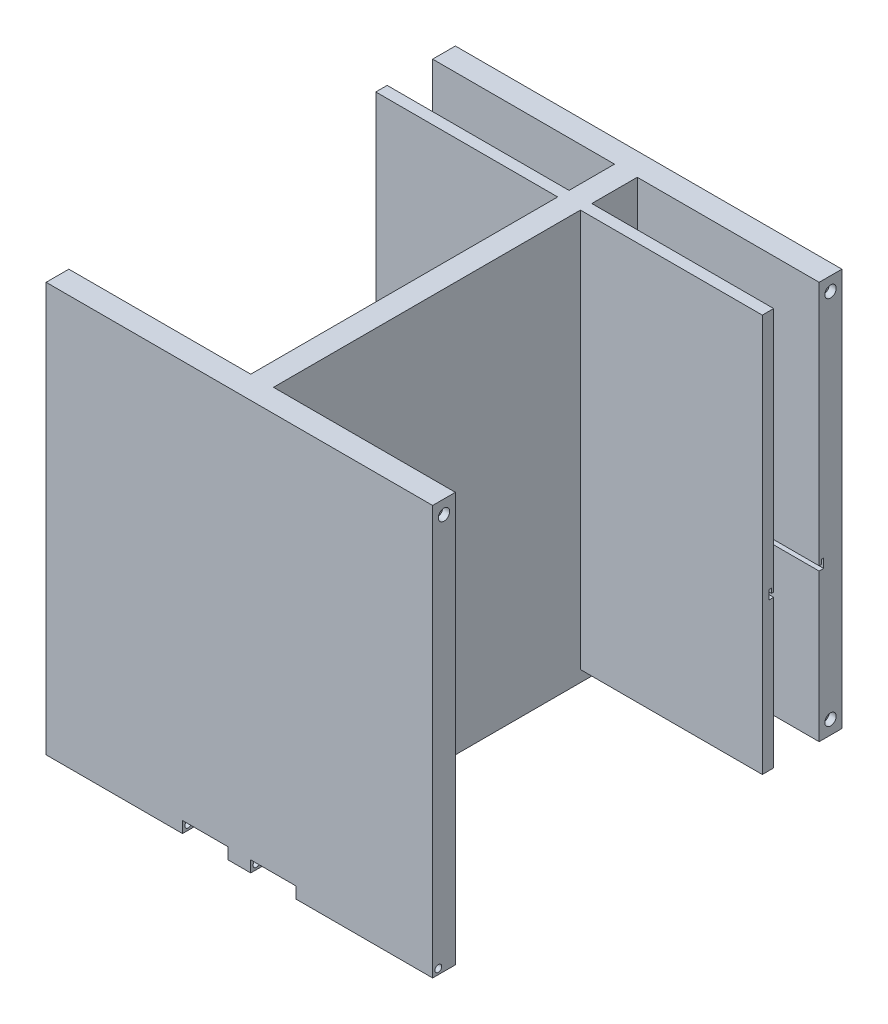
SolidWorks part; units mm, degrees
ref_plane "Front Plane" through (0, 0, 0) normal (0, 0, 1) x (1, 0, 0)
ref_plane "Top Plane" through (0, 0, 0) normal (0, 1, 0) x (1, 0, 0)
ref_plane "Right Plane" through (0, 0, 0) normal (1, 0, 0) x (0, 0, -1)
sketch "Sketch1" plane through (0, 0, 0) normal (0, 1, 0) x (1, 0, 0)
  line L1 (-45, -45) -> (45, -45)
  line L2 (-45, -45) -> (-45, 45)
  line L3 (-45, 45) -> (45, 45)
  line L4 (45, -45) -> (45, 45)
  line L5 (-45, -45) -> (45, 45) construction
  line L6 (-45, 45) -> (45, -45) construction
  point P0 (0, 0)
  dimension "D1" = 90
  dimension "D2" = 90
extrude "Boss-Extrude1" add sketch "Sketch1" along normal blind 90
sketch "Sketch4" plane through (0, 90, 0) normal (0, 1, 0) x (1, 0, 0)
  line L0 (0, 45) -> (0, -45) construction
  line L1 (45, 45) -> (-45, 45) construction
  line L2 (-45, -45) -> (45, -45) construction
  line L3 (-45, 45) -> (-45, -45) construction
  line L4 (-2.5, -40) -> (2.5, -40)
  line L5 (-2.5, -40) -> (-2.5, 40)
  line L6 (-2.5, 40) -> (2.5, 40)
  line L7 (2.5, -40) -> (2.5, 40)
  line L8 (-2.5, -40) -> (2.5, 40) construction
  line L9 (-2.5, 40) -> (2.5, -40) construction
  line L10 (-2.5, 40) -> (-42.5, 40)
  line L11 (-2.5, 40) -> (-2.5, -40)
  line L12 (-2.5, -40) -> (-42.5, -40)
  line L13 (-42.5, 40) -> (-42.5, -40)
  line L14 (2.5, -40) -> (42.5, -40)
  line L15 (42.5, 40) -> (42.5, -40)
  line L16 (2.5, 40) -> (42.5, 40)
  line L17 (2.5, 40) -> (2.5, -40)
  point P6 (0, 0)
  dimension "D1" = 80
  dimension "D2" = 5
  dimension "D3" = 2.5
extrude "Cut-Extrude3" cut sketch "Sketch4" against normal blind 90 contours L12 L13 L10 L5 | L15 L14 L7 L16
sketch "Sketch6" plane through (0, 0, 45) normal (0, 0, 1) x (1, 0, 0)
  line L0 (0, 90) -> (0, 0) construction
  line L1 (-45, 90) -> (45, 90) construction
  line L2 (2.5, 2.5) -> (12.5, 2.5)
  line L3 (-2.5, 0) -> (2.5, 0)
  line L4 (-2.5, 0) -> (-2.5, 90)
  line L5 (-2.5, 90) -> (2.5, 90)
  line L6 (2.5, 0) -> (2.5, 90)
  line L7 (-2.5, 0) -> (2.5, 90) construction
  line L8 (-2.5, 90) -> (2.5, 0) construction
  line L9 (-2.5, 0) -> (-12.5, 0)
  line L10 (-2.5, 0) -> (-2.5, 2.5)
  line L11 (-2.5, 2.5) -> (-12.5, 2.5)
  line L12 (-12.5, 0) -> (-12.5, 2.5)
  line L13 (12.5, 0) -> (12.5, 2.5)
  line L14 (2.5, 0) -> (12.5, 0)
  line L15 (2.5, 0) -> (2.5, 2.5)
  point P5 (0, 45)
  dimension "D1" = 5
  dimension "D2" = 2.5
  dimension "D3" = 10
extrude "Cut-Extrude5" cut sketch "Sketch6" against normal blind 10 contours L15 L2 L13 L14 | L10 L11 L12 L9
sketch "Sketch7" plane through (0, 90, 0) normal (0, 1, 0) x (1, 0, 0)
  line L0 (42.5, 40) -> (42.5, 45)
  line L1 (45, 45) -> (-45, 45) construction
  line L2 (42.5, -40) -> (42.5, -45)
  line L3 (-45, -45) -> (45, -45) construction
  line L4 (42.5, 45) -> (45, 45)
  line L5 (45, 45) -> (45, -45)
  line L6 (45, -45) -> (42.5, -45)
  line L7 (42.5, 40) -> (42.5, -40)
extrude "Cut-Extrude6" cut sketch "Sketch7" against normal blind 90 contours L4 L5 L6 L2 L7 L0
sketch "Sketch8" plane through (0, 90, 0) normal (0, 1, 0) x (1, 0, 0)
  line L0 (-42.5, 40) -> (-42.5, 45)
  line L1 (42.5, 45) -> (-45, 45) construction
  line L2 (-42.5, 45) -> (-45, 45)
  line L3 (-45, 45) -> (-45, -45)
  line L4 (-45, -45) -> (-42.5, -45)
  line L5 (-45, -45) -> (42.5, -45) construction
  line L6 (-42.5, -45) -> (-42.5, -42.5)
  line L7 (-42.5, 40) -> (-42.5, -40) construction
  line L8 (-42.5, -42.5) -> (-42.5, 40)
extrude "Cut-Extrude7" cut sketch "Sketch8" against normal blind 90
sketch "Sketch10" plane through (-2.5, 0, 0) normal (-1, 0, 0) x (0, 0, 1)
  line L0 (40, 90) -> (-40, 90) construction
  line L1 (-27.5, 90) -> (-30, 90)
  line L2 (-27.5, 90) -> (-27.5, 0)
  line L3 (-27.5, 0) -> (-30, 0)
  line L4 (-30, 90) -> (-30, 0)
  line L5 (45, 0) -> (-40, 0) construction
  line L6 (-40, 0) -> (-40, 90) construction
  dimension "D1" = 10
  dimension "D2" = 2.5
extrude "Boss-Extrude2" add sketch "Sketch10" along normal blind 40 contours L1 L4 L3 L2
sketch "Sketch11" plane through (2.5, 0, 0) normal (1, 0, 0) x (0, 0, -1)
  line L0 (-45, 0) -> (40, 0) construction
  line L1 (27.5, 90) -> (30, 90)
  line L2 (27.5, 90) -> (27.5, 0)
  line L3 (27.5, 0) -> (30, 0)
  line L4 (30, 90) -> (30, 0)
  line L5 (40, 0) -> (40, 90) construction
  dimension "D1" = 10
  dimension "D2" = 2.5
extrude "Boss-Extrude3" add sketch "Sketch11" along normal blind 40
sketch "Sketch13" plane through (42.5, 0, 0) normal (1, 0, 0) x (0, 0, -1)
  line L0 (35, 90) -> (35, 0) construction
  line L1 (30, 90) -> (40, 90) construction
  line L2 (30, 0) -> (40, 0) construction
  line L13 (40, 36) -> (40.5, 36)
  line L14 (40, 0) -> (40, 90) construction
  line L15 (40.5, 36) -> (40.5, 37)
  line L16 (40.5, 37) -> (41, 37)
  line L17 (41, 37) -> (41, 35)
  line L18 (41, 35) -> (40, 35)
  line L19 (40, 35) -> (40, 36)
  line L20 (40, 0) -> (45, 0) construction
  line L21 (29, 35) -> (30, 35)
  line L22 (29, 37) -> (29, 35)
  line L23 (29.5, 37) -> (29, 37)
  line L24 (29.5, 36) -> (29.5, 37)
  line L25 (30, 36) -> (29.5, 36)
  line L26 (30, 35) -> (30, 36)
  dimension "D1" = 2
  dimension "D2" = 1
  dimension "D3" = 0.5
  dimension "D4" = 35
  dimension "D5" = 1
extrude "Cut-Extrude10" cut sketch "Sketch13" against normal blind 37.5 contours L13 L15 L16 L17 L18 L19 | L22 L21 L26 L25 L24 L23
ref_plane "Plane1" through (0, 0, 0) normal (-1, 0, 0) x (0, 0, 1)
mirror "Mirror1" about plane through (0, 0, 0) normal (-1, 0, 0) of "Cut-Extrude10"
sketch "Sketch16" plane through (-12.5, 0, 0) normal (1, 0, 0) x (0, 0, -1)
  line L0 (-40, 0) -> (-45, 0) construction
  line L1 (-45, 0) -> (-45, 2.5) construction
  circle A0 centre (-43.75, 1.2) radius 0.75
  dimension "D1" = 1.5
  dimension "D2" = 1.2
  dimension "D3" = 1.25
extrude "Cut-Extrude12" cut sketch "Sketch16" against normal blind 1.5
sketch "Sketch17" plane through (-2.5, 0, 0) normal (-1, 0, 0) x (0, 0, 1)
  line L0 (45, 0) -> (45, 2.5) construction
  line L1 (45, 0) -> (-27.5, 0) construction
  circle A0 centre (43.75, 1.2) radius 0.75
  dimension "D1" = 1.5
  dimension "D2" = 1.25
  dimension "D3" = 1.2
extrude "Cut-Extrude13" cut sketch "Sketch17" along normal through all both and the other way through all
sketch "Sketch21" plane through (42.5, 0, 0) normal (1, 0, 0) x (0, 0, -1)
  line L0 (-40, 0) -> (-40, 2.5)
  line L1 (-45, 0) -> (27.5, 0) construction
  line L2 (-40, 2.5) -> (-40, 90) construction
  line L3 (-40, 2.5) -> (45, 2.5)
  line L4 (45, 0) -> (45, 90) construction
  line L5 (45, 2.5) -> (45, 0)
  line L6 (45, 0) -> (-40, 0)
  line L7 (-45, 0) -> (-40, 0) construction
  point P6 (-40, 0)
  dimension "D1" = 2.5
extrude "Cut-Extrude14" cut sketch "Sketch21" against normal blind 40
sketch "Sketch22" plane through (-42.5, 0, 0) normal (-1, 0, 0) x (0, 0, 1)
  line L6 (40, 0) -> (40, 2.5)
  line L7 (40, 2.5) -> (40, 90) construction
  line L8 (40, 2.5) -> (-45, 2.5)
  line L9 (-45, 0) -> (-45, 90) construction
  line L10 (-45, 2.5) -> (-45, 0)
  line L11 (-45, 0) -> (40, 0)
  dimension "D1" = 2.5
extrude "Cut-Extrude15" cut sketch "Sketch22" against normal blind 40
sketch "Sketch23" plane through (42.5, 0, 0) normal (1, 0, 0) x (0, 0, -1)
  line L0 (42.5, 90) -> (42.5, 2.5) construction
  line L1 (45, 90) -> (40, 90) construction
  line L2 (45, 2.5) -> (40, 2.5) construction
  line L3 (45, 2.5) -> (45, 90) construction
  line L4 (45, 46.25) -> (40, 46.25) construction
  line L5 (40, 2.5) -> (40, 90) construction
  circle A0 centre (42.5, 87) radius 1.25
  circle A1 centre (42.5, 5.5) radius 1.25
  dimension "D3" = 2.5
  dimension "D1" = 2.5
  dimension "D2" = 3
extrude "Cut-Extrude16" cut sketch "Sketch23" against normal blind 1.5
sketch "Sketch24" plane through (42.5, 0, 0) normal (1, 0, 0) x (0, 0, -1)
  line L0 (-42.8174, 90) -> (-42.5, 90) construction
  line L1 (-40, 90) -> (-45, 90) construction
  line L2 (-42.5, 90) -> (-42.5, 0) construction
  line L3 (-45, 0) -> (-40, 0) construction
  circle A0 centre (-42.5, 87) radius 1.25
  dimension "D1" = 2.5
  dimension "D2" = 3
extrude "Cut-Extrude17" cut sketch "Sketch24" against normal blind 1.5
mirror "Mirror2" about plane through (0, 0, 0) normal (-1, 0, 0) of "Cut-Extrude16", "Cut-Extrude17"
equation "\"length\"= 90mm"
equation "\"D1@Sketch1\"=\"length\""
equation "\"D2@Sketch1\"=\"length\""
equation "\"depth\"= 90"
equation "\"D1@Boss-Extrude1\"=\"depth\""
equation "\"D1@Sketch4\"=80"
equation "\"D1@Cut-Extrude3\"=\"depth\""
equation "\"D1@Cut-Extrude6\"=\"depth\""
equation "\"D1@Cut-Extrude7\"=\"depth\""
equation "\"D1@Boss-Extrude2\"=45-5"
